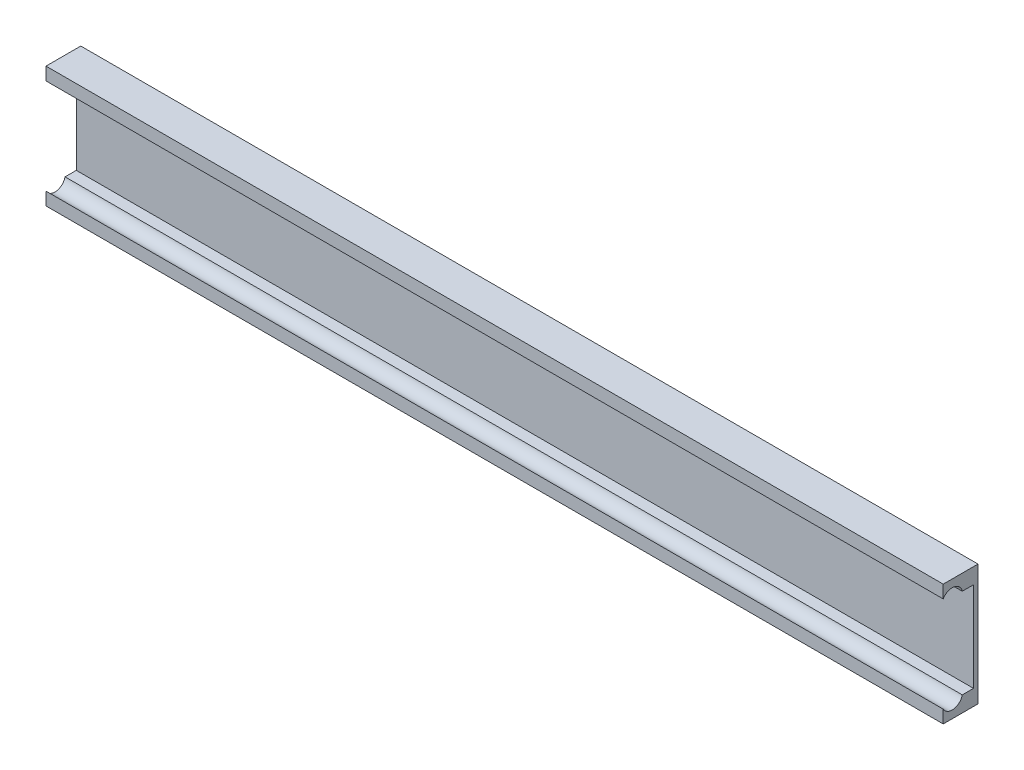
SolidWorks part; units mm, degrees
ref_plane "Front" through (0, 0, 0) normal (0, 0, 1) x (1, 0, 0)
ref_plane "Top" through (0, 0, 0) normal (0, 1, 0) x (1, 0, 0)
ref_plane "Right" through (0, 0, 0) normal (1, 0, 0) x (0, 0, -1)
sketch "Sketch1" plane through (0, 0, 0) normal (0, 0, 1) x (1, 0, 0)
  line L0 (-100, -4) -> (-100, 4) construction
  line L1 (100, -13.5) -> (-100, -13.5)
  line L2 (100, -13.5) -> (100, 13.5)
  line L3 (100, 13.5) -> (-100, 13.5)
  line L4 (-100, -13.5) -> (-100, 13.5)
  line L5 (100, -13.5) -> (-100, 13.5) construction
  line L6 (100, 13.5) -> (-100, -13.5) construction
  line L8 (100, 9) -> (-100, 9) construction
  point P0 (0, 0)
  dimension "D1" = 4.5
extrude "Boss-Extrude1" add sketch "Sketch1" against normal blind 1
sketch "Sketch2" plane through (0, 0, 0) normal (0, 0, 1) x (1, 0, 0)
  line L0 (-100, -13.5) -> (-100, 13.5) construction
  line L1 (100, 13.5) -> (-100, 13.5)
  line L2 (100, 13.5) -> (100, 10)
  line L3 (100, 10) -> (-100, 10)
  line L4 (-100, 13.5) -> (-100, 10)
  line L6 (100, -13.5) -> (-100, -13.5)
  line L7 (100, -13.5) -> (100, -10)
  line L8 (100, -10) -> (-100, -10)
  line L9 (-100, -13.5) -> (-100, -10)
  line L10 (-100, -13.5) -> (-100, 13.5) construction
  line L12 (100, 9) -> (-100, 9) construction
  dimension "D1" = 1
extrude "Boss-Extrude2" add sketch "Sketch2" along normal up to surface (6.75 mm away)
sketch "Sketch3" plane through (0, 0, 0) normal (1, 0, 0) x (0, 0, -1)
  circle A1 centre (-4.75, 9.5) radius 2.3
  circle A2 centre (-4.75, 9.5) radius 2.3
  dimension "D1" = 0
extrude "Top Slot" cut sketch "Sketch3" against normal through all both and the other way through all
mirror "Bottom Slot" about plane through (0, 0, 0) normal (0, 1, 0) of "Top Slot"
